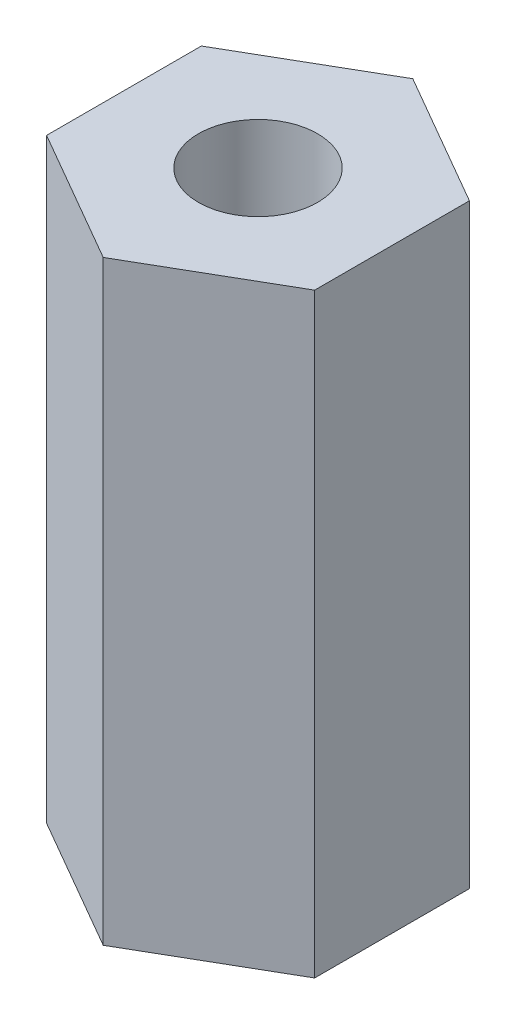
SolidWorks part; units mm, degrees
ref_plane "Front Plane" through (0, 0, 0) normal (0, 0, 1) x (1, 0, 0)
ref_plane "Top Plane" through (0, 0, 0) normal (0, 1, 0) x (1, 0, 0)
ref_plane "Right Plane" through (0, 0, 0) normal (1, 0, 0) x (0, 0, -1)
sketch "Sketch1" plane through (0, 0, 0) normal (0, 1, 0) x (1, 0, 0)
  line L0 (0, 0) -> (0, 2.5981) construction
  line L1 (0, 2.5981) -> (-2.25, 1.299)
  line L2 (-2.25, 1.299) -> (-2.25, -1.299)
  line L3 (-2.25, -1.299) -> (0, -2.5981)
  line L4 (0, -2.5981) -> (2.25, -1.299)
  line L5 (2.25, -1.299) -> (2.25, 1.299)
  line L6 (2.25, 1.299) -> (0, 2.5981)
  circle A0 centre (0, 0) radius 2.25 construction
  circle A1 centre (0, 0) radius 1
  dimension "D2" = 2
  dimension "D1" = 4.5
extrude "Boss-Extrude1" add sketch "Sketch1" along normal blind 10
